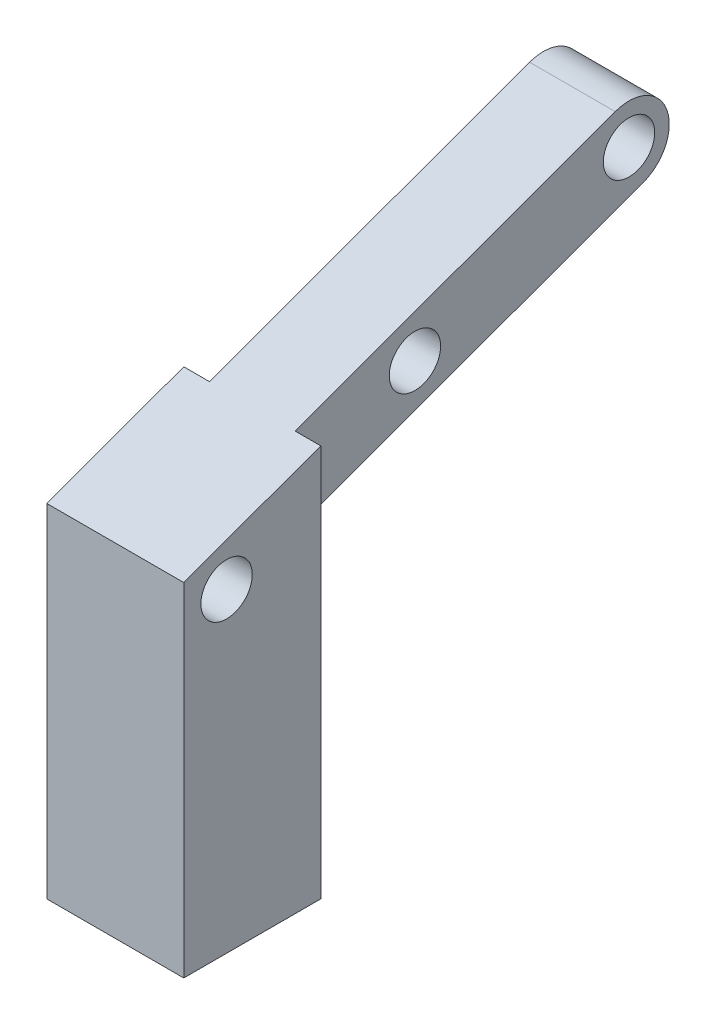
SolidWorks part; units mm, degrees
ref_plane "前视基准面" through (0, 0, 0) normal (0, 0, 1) x (1, 0, 0)
ref_plane "上视基准面" through (0, 0, 0) normal (0, 1, 0) x (1, 0, 0)
ref_plane "右视基准面" through (0, 0, 0) normal (1, 0, 0) x (0, 0, -1)
other "Configuration Table"
sketch "草图1" plane through (0, 0, 0) normal (0, 1, 0) x (1, 0, 0)
  line L1 (4, -4) -> (-4, -4)
  line L2 (4, -4) -> (4, 4)
  line L3 (4, 4) -> (-4, 4)
  line L4 (-4, -4) -> (-4, 4)
  line L5 (4, -4) -> (-4, 4) construction
  line L6 (4, 4) -> (-4, -4) construction
  point P0 (0, 0)
  point P3 (0, 0)
  dimension "D2" = 8
extrude "凸台-拉伸1" add sketch "草图1" along normal blind 20
sketch "草图2" plane through (0, 0, 0) normal (1, 0, 0) x (0, 0, -1)
  line L1 (-4, 20) -> (26, 30.9191)
  line L2 (-4, 20) -> (-4, 15)
  line L3 (-4, 15) -> (26, 25.9191)
  line L4 (26, 30.9191) -> (26, 25.9191)
  dimension "D1" = 5
  dimension "D3" = 30
extrude "凸台-拉伸2" add sketch "草图2" along normal mid plane 5
sketch "草图4" plane through (2.5, 0, 0) normal (1, 0, 0) x (0, 0, -1)
  line L0 (-4, 17.5) -> (26, 28.4191) construction
  line L2 (26, 25.9191) -> (26, 30.9191) construction
  circle A0 centre (-1.5, 18.4099) radius 1.5
  circle A1 centre (23.5, 27.5092) radius 1.5
  circle A2 centre (11, 22.9596) radius 1.5
  point P10 (0, 0)
  point P15 (0, 0)
  dimension "D1" = 3
  dimension "D2" = 3
  dimension "D4" = 2.5
  dimension "D5" = 3
extrude "切除-拉伸1" cut sketch "草图4" against normal through all both and the other way through all
sketch "草图7" plane through (-2.5, 0, 0) normal (-1, 0, 0) x (0, 0, 1)
  line L5 (-26, 25.9191) -> (-4, 17.9118)
  line L6 (-4, 17.9118) -> (-4, 20)
  line L7 (-4, 17.9118) -> (-4, 20)
  line L8 (4, 20) -> (-26, 30.9191)
  line L9 (-26, 30.9191) -> (-26, 25.9191)
  line L10 (-26, 25.9191) -> (-4, 17.9118)
  line L13 (4, 20) -> (-26, 30.9191)
  line L14 (-26, 30.9191) -> (-26, 25.9191)
  line L18 (-4, 20) -> (4, 20)
  line L19 (-4, 20) -> (4, 20)
  circle A0 centre (-23.5, 27.5092) radius 2.3492
  line M9 (-26, 25.9191) -> (-4, 17.9118)
  line M13 (-26, 30.9191) -> (-26, 25.9191)
  dimension "D1" = 0
extrude "切除-拉伸2" cut sketch "草图7" against normal through all contours A0 L13 M13 M9
sketch "草图9" plane through (0, 0, 0) normal (0, -1, 0) x (1, 0, 0)
  circle A0 centre (0, 0) radius 1.3
  dimension "D1" = 2.6
extrude "切除-拉伸3" cut sketch "草图9" against normal blind 10
sketch "草图11" plane through (4, 0, 0) normal (1, 0, 0) x (0, 0, -1)
  line L0 (4, 20) -> (4, 22.9118)
  line L4 (4, 17.9118) -> (24.3035, 25.3016)
  line L5 (22.6965, 29.7167) -> (-4, 20)
  line L6 (-4, 20) -> (4, 20)
  line L7 (4, 20) -> (4, 17.9118)
  line L8 (4, 17.9118) -> (24.3035, 25.3016)
  line L9 (22.6965, 29.7167) -> (-4, 20)
  line L10 (-4, 20) -> (4, 20)
  line L11 (4, 20) -> (4, 17.9118)
  arc A1 (24.3035, 25.3016) -> (22.6965, 29.7167) centre (23.5, 27.5092) ccw
  arc A2 (24.3035, 25.3016) -> (22.6965, 29.7167) centre (23.5, 27.5092) ccw
  line M9 (4, 20) -> (-4, 20)
  dimension "D1" = 0
extrude "凸台-拉伸3" add sketch "草图11" against normal up to surface (8 mm away) contours L0 L9 M9 up to face at (-4, 18.4099, 0)
sketch "草图12" plane through (0, 0, 0) normal (0, -1, 0) x (1, 0, 0)
  line L1 (2.8406, 0) -> (1.4203, 2.46)
  line L2 (1.4203, 2.46) -> (-1.4203, 2.46)
  line L3 (-1.4203, 2.46) -> (-2.8406, 0)
  line L4 (-2.8406, 0) -> (-1.4203, -2.46)
  line L5 (-1.4203, -2.46) -> (1.4203, -2.46)
  line L6 (1.4203, -2.46) -> (2.8406, 0)
  circle A0 centre (0, 0) radius 2.46 construction
  dimension "D1" = 4.92
extrude "切除-拉伸4" cut sketch "草图12" against normal blind 3.55 from offset 4
